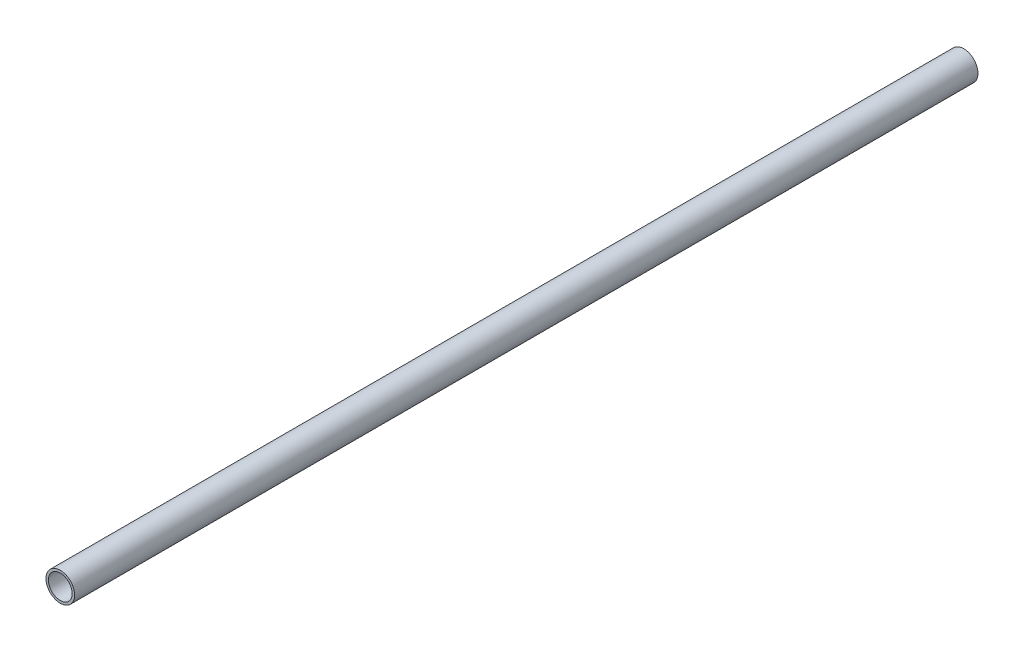
SolidWorks part; units mm, degrees
ref_plane "Front Plane" through (0, 0, 0) normal (0, 0, 1) x (1, 0, 0)
ref_plane "Top Plane" through (0, 0, 0) normal (0, 1, 0) x (1, 0, 0)
ref_plane "Right Plane" through (0, 0, 0) normal (1, 0, 0) x (0, 0, -1)
sketch "Sketch1" plane through (0, 0, 0) normal (1, 0, 0) x (0, 0, -1)
  line L0 (0, 0) -> (300, 0) construction
  line L2 (0, 3.95) -> (300, 3.95)
  line L3 (0, 3.95) -> (0, 4.75)
  line L4 (0, 4.75) -> (300, 4.75)
  line L5 (300, 3.95) -> (300, 4.75)
  dimension "D1" = 300
  dimension "D2" = 9.5
  dimension "D3" = 0.8
revolve "Revolve1" add sketch "Sketch1" angle 360 about L0
